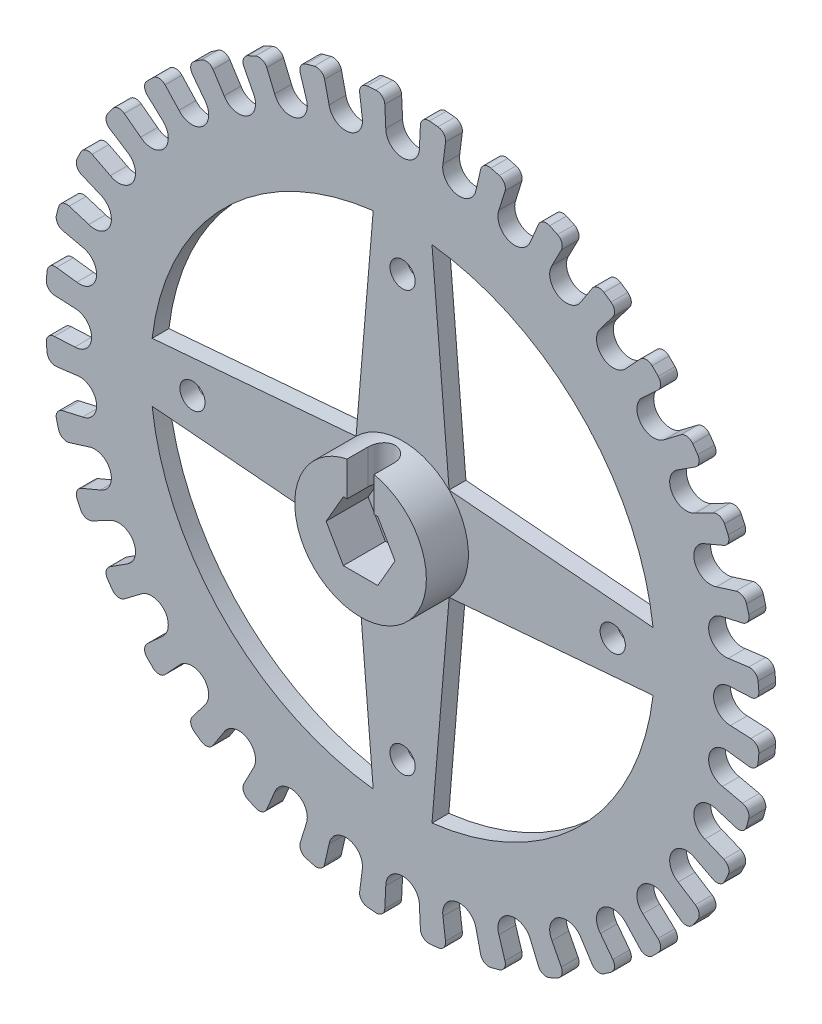
SolidWorks part; units mm, degrees
ref_plane "Front Plane" through (0, 0, 0) normal (0, 0, 1) x (1, 0, 0)
ref_plane "Top Plane" through (0, 0, 0) normal (0, 1, 0) x (1, 0, 0)
ref_plane "Right Plane" through (0, 0, 0) normal (1, 0, 0) x (0, 0, -1)
sketch "Sketch1" plane through (0, 0, 0) normal (0, 0, 1) x (1, 0, 0)
  line L0 (0, 0) -> (0, 6) construction
  line L1 (0, 25) -> (1.65, 25) construction
  line L2 (-1.65, 27.0934) -> (1.65, 27.0934) construction
  line L3 (-1.65, 27.0934) -> (-1.65, 38.3614) construction
  line L4 (-1.65, 38.3614) -> (1.65, 38.3614) construction
  line L5 (1.65, 27.0934) -> (1.65, 38.3614) construction
  line L6 (-3.4971, 29.7955) -> (-5.535, 5.535)
  line L7 (1.5588, 0) -> (0.7794, 1.35)
  line L8 (0.7794, 1.35) -> (-0.7794, 1.35)
  line L9 (-0.7794, 1.35) -> (-1.5588, 0)
  line L10 (-1.5588, 0) -> (-0.7794, -1.35)
  line L11 (-0.7794, -1.35) -> (0.7794, -1.35)
  line L12 (0.7794, -1.35) -> (1.5588, 0)
  line L13 (3.4971, 29.7955) -> (5.535, 5.535)
  line L14 (29.7955, 3.4971) -> (5.535, 5.535)
  line L15 (29.7955, -3.4971) -> (5.535, -5.535)
  line L16 (3.4971, -29.7955) -> (5.535, -5.535)
  line L17 (-3.4971, -29.7955) -> (-5.535, -5.535)
  line L18 (-29.7955, -3.4971) -> (-5.535, -5.535)
  line L19 (-29.7955, 3.4971) -> (-5.535, 5.535)
  line L20 (3.8999, 25) -> (12.5438, 25) construction
  line L27 (0, 23.5) -> (0, 76.7228) construction
  circle A0 centre (0, 0) radius 42.5
  circle A2 centre (0, 25) radius 1.5
  arc A3 (-3.4971, 29.7955) -> (-29.7955, 3.4971) centre (0, 0) ccw
  circle A4 centre (0, 0) radius 1.35 construction
  circle A5 centre (25, 0) radius 1.5
  circle A6 centre (0, -25) radius 1.5
  circle A7 centre (-25, 0) radius 1.5
  arc A8 (-29.7955, -3.4971) -> (-3.4971, -29.7955) centre (0, 0) ccw
  arc A9 (3.4971, -29.7955) -> (29.7955, -3.4971) centre (0, 0) ccw
  arc A10 (29.7955, 3.4971) -> (3.4971, 29.7955) centre (0, 0) ccw
  point P7 (0, 42.5)
  point P10 (0, 38.3614)
  dimension "D1" = 85
  dimension "D2" = 25
  dimension "D3" = 3
  dimension "D6" = 2.7
  dimension "D4" = 3.3
  dimension "D5" = 0
  dimension "D8" = 4
extrude "Boss-Extrude1" add sketch "Sketch1" along normal blind 2
sketch "Sketch2" plane through (0, 0, 2) normal (0, 0, 1) x (1, 0, 0)
  line L0 (0, 0) -> (0, 46.0615) construction
  line L1 (-2, 39) -> (-2.25, 44.1517)
  line L2 (-2.25, 44.1517) -> (2.25, 44.1517)
  line L3 (2.25, 44.1517) -> (2, 39)
  arc A0 (-2, 39) -> (2, 39) centre (0, 39) ccw
  circle A1 centre (0, 0) radius 42.5 construction
  point P4 (0, 44.1517)
  point P5 (0, 42.5)
  dimension "D1" = 3.5
  dimension "D3" = 2.25
  dimension "D2" = 2
extrude "Cut-Extrude1" cut sketch "Sketch2" against normal through all
sketch "Sketch5" plane through (0, 0, 2) normal (0, 0, 1) x (1, 0, 0)
  line L0 (3.8898, 40.5) -> (-1.3229, 40.5) construction
  line L1 (0, 42.5) -> (3.8939, 42.5) construction
  line L4 (-2, 39) -> (-2.1672, 42.4447)
  line L5 (-2, 39) -> (-2.1672, 42.4447)
  line L6 (2.1672, 42.4447) -> (2, 39)
  line L7 (2.1672, 42.4447) -> (2, 39)
  circle A0 centre (0, 39) radius 2 construction
  circle A1 centre (0, 0) radius 42.5 construction
  arc A3 (-2.1672, 42.4447) -> (2.1672, 42.4447) centre (0, 0) ccw
  arc A4 (-2.1672, 42.4447) -> (2.1672, 42.4447) centre (0, 0) ccw
  arc A194 (-2, 39) -> (2, 39) centre (0, 39) ccw
  arc A195 (-2, 39) -> (2, 39) centre (0, 39) ccw
  dimension "D1" = 0
  dimension "D2" = 2
fillet "Fillet1" radius 1 2 edges at (-2.1672, 42.4447, 1) (2.1672, 42.4447, 1)
pattern_circular "CirPattern1" count 36 over 360 about axis through (0, 0, 0) along (0, 0, 1) of "Fillet1", "Cut-Extrude1"
sketch "Sketch6" plane through (0, 0, 2) normal (0, 0, 1) x (1, 0, 0)
  circle A0 centre (0, 0) radius 7.8277
extrude "Boss-Extrude2" add sketch "Sketch6" along normal blind 5
sketch "Sketch7" plane through (0, 0, 7) normal (0, 0, 1) x (1, 0, 0)
  line L1 (4.0992, 0) -> (2.0496, 3.55)
  line L2 (2.0496, 3.55) -> (-2.0496, 3.55)
  line L3 (-2.0496, 3.55) -> (-4.0992, 0)
  line L4 (-4.0992, 0) -> (-2.0496, -3.55)
  line L5 (-2.0496, -3.55) -> (2.0496, -3.55)
  line L6 (2.0496, -3.55) -> (4.0992, 0)
  circle A0 centre (0, 0) radius 3.55 construction
  dimension "D1" = 7.1
extrude "Cut-Extrude2" cut sketch "Sketch7" against normal blind 5
sketch "Sketch8" plane through (0, 3.55, 0) normal (0, -1, 0) x (1, 0, 0)
  line L2 (1.6, 4.5) -> (1.6, 7.9519)
  line L3 (1.6, 7.9519) -> (-1.6, 7.9519)
  line L4 (-1.6, 4.5) -> (-1.6, 7.9519)
  arc A0 (-1.6, 4.5) -> (1.6, 4.5) centre (0, 4.5) ccw
extrude "Cut-Extrude3" cut sketch "Sketch8" against normal blind 5
